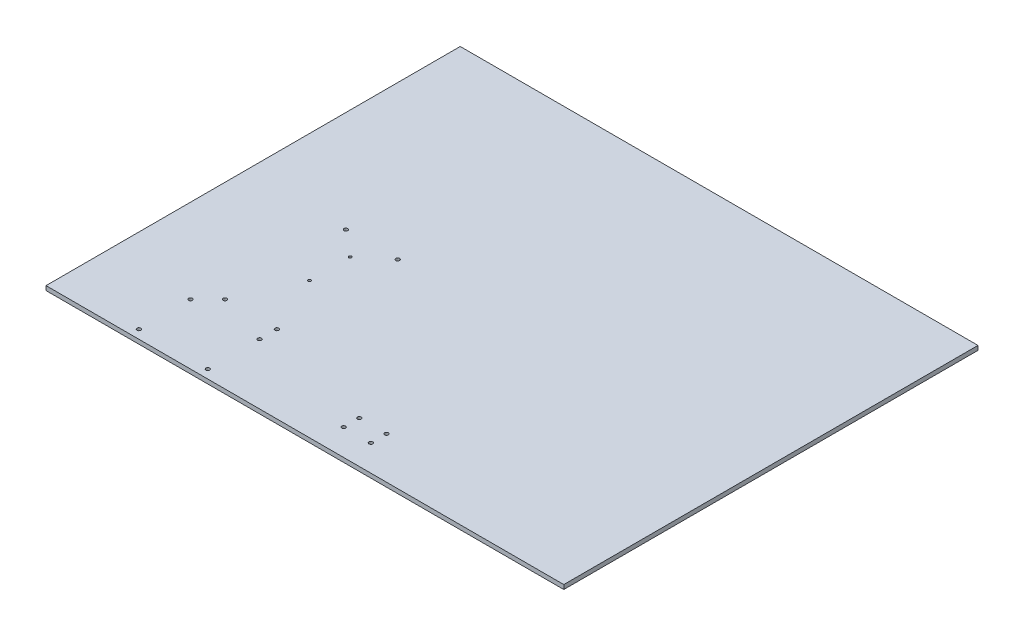
SolidWorks part; units mm, degrees
material "6061 Alloy"
ref_plane "Front" through (0, 0, 0) normal (0, 0, 1) x (1, 0, 0)
ref_plane "Top" through (0, 0, 0) normal (0, 1, 0) x (1, 0, 0)
ref_plane "Right" through (0, 0, 0) normal (1, 0, 0) x (0, 0, -1)
sketch "Sketch1" plane through (0, 0, 0) normal (0, 1, 0) x (1, 0, 0)
  line L1 (0, 0) -> (762, 0)
  line L2 (0, 0) -> (0, 609.6)
  line L3 (0, 609.6) -> (762, 609.6)
  line L4 (762, 0) -> (762, 609.6)
  dimension "D1" = 609.6
  dimension "D2" = 762
extrude "Boss-Extrude1" add sketch "Sketch1" along normal blind 6.35
hole_wizard "M5 Clearance Hole1" positions "Sketch3" profile "Sketch4" hole size "M5" standard "ANSI Metric" end condition through all
sketch "Sketch3" plane through (0, 6.35, 0) normal (0, 1, 0) x (1, 0, 0)
  line L0 (762, 0) -> (762, 609.6) construction
  line L1 (0, 0) -> (762, 0) construction
  point P0 (439.4454, 61.6712)
  point P2 (399.4404, 61.6712)
  point P4 (399.4404, 38.6588)
  point P6 (439.4454, 38.6588)
  dimension "D1" = 322.5546
  dimension "D2" = 40.005
  dimension "D3" = 23.0124
  dimension "D4" = 40.005
  dimension "D5" = 23.0124
  dimension "D6" = 38.6588
sketch "Sketch4" plane through (439.4454, 6.35, -61.6712) normal (1, 0, 0) x (0, 0, 1)
  line L0 (0, 0) -> (0, 6.35)
  line L1 (0, 6.35) -> (2.75, 6.35)
  line L2 (2.75, 6.35) -> (2.75, 0)
  line L5 (2.75, 0) -> (0, 0)
  line L11 (0, -6.35) -> (0, 107.95) construction
  dimension "Thru Hole Dia." = 5.5
  dimension "Thru Hole Depth" = 6.35
hole_wizard "M5 Clearance Hole2" positions "Sketch7" profile "Sketch8" hole size "M5" standard "ANSI Metric" end condition through all
sketch "Sketch7" plane through (0, 6.35, 0) normal (0, 1, 0) x (1, 0, 0)
  line L2 (0, 0) -> (762, 0) construction
  line L3 (0, 609.6) -> (0, 0) construction
  point P0 (123.8758, 12.7)
  point P2 (225.4758, 12.7)
  point P4 (225.4758, 88.9)
  point P6 (123.8758, 88.9)
  point P19 (225.4758, 114.3)
  point P22 (225.4758, 292.1)
  point P25 (225.4758, 292.1)
  point P27 (149.2758, 292.1)
  point P29 (149.2758, 114.3)
  dimension "D1" = 123.8758
  dimension "D2" = 101.6
  dimension "D3" = 123.8758
  dimension "D4" = 101.6
  dimension "D5" = 25.4
  dimension "D6" = 12.7
  dimension "D7" = 177.8
  dimension "D8" = 76.2
  dimension "D9" = 76.2
sketch "Sketch8" plane through (123.8758, 6.35, -12.7) normal (1, 0, 0) x (0, 0, 1)
  line L0 (0, 0) -> (0, 6.35)
  line L1 (0, 6.35) -> (2.75, 6.35)
  line L2 (2.75, 6.35) -> (2.75, 0)
  line L5 (2.75, 0) -> (0, 0)
  line L11 (0, -6.35) -> (0, 107.95) construction
  dimension "Thru Hole Dia." = 5.5
  dimension "Thru Hole Depth" = 6.35
sketch "Sketch14" plane through (0, 6.35, 0) normal (0, 1, 0) x (1, 0, 0)
  line L0 (149.2758, 292.1) -> (225.4758, 292.1) construction
hole_wizard "M5x0.8 Tapped Hole2" positions "Sketch15" profile "Sketch16" tap size "M5x0.8" standard "ANSI Metric" end condition through all
sketch "Sketch15" plane through (0, 6.35, 0) normal (0, 1, 0) x (1, 0, 0)
  line L0 (149.2758, 292.1) -> (225.4758, 292.1) construction
  point P0 (187.3758, 260.35)
  point P2 (187.3758, 200.3552)
  dimension "D1" = 31.75
  dimension "D2" = 59.9948
sketch "Sketch16" plane through (187.3758, 6.35, -260.35) normal (1, 0, 0) x (0, 0, 1)
  line L0 (0, 0) -> (0, 6.35)
  line L1 (0, 6.35) -> (2.1, 6.35)
  line L2 (2.1, 6.35) -> (2.1, 0)
  line L5 (2.1, 0) -> (0, 0)
  line L11 (0, -6.35) -> (0, 107.95) construction
  dimension "Thru Tap Drill Dia." = 4.2
  dimension "Thru Tap Drill Depth" = 6.35
cosmetic thread "Hole Thread7"
cosmetic thread "Hole Thread8"
